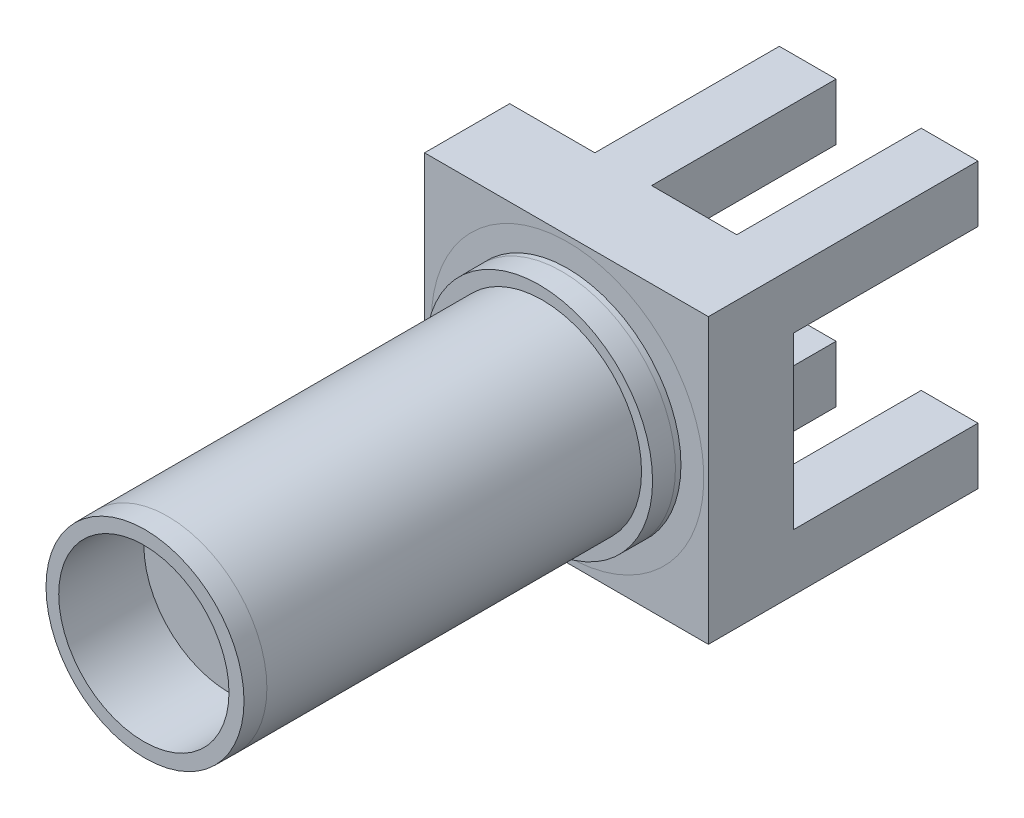
SolidWorks part; units mm, degrees
ref_plane "Front Plane" through (0, 0, 0) normal (0, 0, 1) x (1, 0, 0)
ref_plane "Top Plane" through (0, 0, 0) normal (0, 1, 0) x (1, 0, 0)
ref_plane "Right Plane" through (0, 0, 0) normal (1, 0, 0) x (0, 0, -1)
sketch "Sketch1" plane through (0, 0, 0) normal (0, 0, 1) x (1, 0, 0)
  line L1 (-1.1462, 0) -> (-11.1462, 0)
  line L2 (-1.1462, 0) -> (-1.1462, 10)
  line L3 (-1.1462, 10) -> (-11.1462, 10)
  line L4 (-11.1462, 0) -> (-11.1462, 10)
  dimension "D1" = 10
  dimension "D2" = 10
extrude "Boss-Extrude1" add sketch "Sketch1" along normal blind 3 contours L2 L1 L4 L3
sketch "Sketch2" plane through (0, 0, 0) normal (0, 0, 1) x (1, 0, 0)
  line L0 (-1.1462, 10) -> (-11.1462, 10) construction
  line L2 (-1.1462, 0) -> (-1.1462, 10) construction
  circle A0 centre (-6.1462, 5) radius 2.5
  dimension "D1" = 5
  dimension "D2" = 5
  dimension "D3" = 5
revolve "Cut-Revolve1" cut sketch "Sketch2" angle 7 about axis through (-1.1462, 0, 0) along (0, 1, 0)
sketch "Sketch3" plane through (0, 0, 0) normal (0, 0, -1) x (-1, 0, 0)
  line L1 (1.1462, 0) -> (3.1462, 0)
  line L2 (1.1462, 0) -> (1.1462, 2)
  line L3 (1.1462, 2) -> (3.1462, 2)
  line L4 (3.1462, 0) -> (3.1462, 2)
  dimension "D1" = 2
  dimension "D2" = 2
extrude "Boss-Extrude2" add sketch "Sketch3" along normal blind 6.5 contours L2 L1 L4 L3
sketch "Sketch4" plane through (0, 0, 0) normal (0, 0, -1) x (-1, 0, 0)
  line L1 (3.1462, 0) -> (11.1462, 0) construction
  line L3 (6.1462, 0) -> (8.1462, 0)
  line L4 (6.1462, 0) -> (6.1462, 2)
  line L5 (6.1462, 2) -> (8.1462, 2)
  line L6 (8.1462, 0) -> (8.1462, 2)
  dimension "D2" = 2
  dimension "D3" = 2
extrude "Boss-Extrude3" add sketch "Sketch4" along normal blind 6.5 contours L4 L3 L6 L5
sketch "Sketch5" plane through (0, 0, 0) normal (0, 0, -1) x (-1, 0, 0)
  line L2 (1.1462, 10) -> (3.1462, 10)
  line L3 (1.1462, 10) -> (1.1462, 8)
  line L4 (1.1462, 8) -> (3.1462, 8)
  line L5 (3.1462, 10) -> (3.1462, 8)
  line L6 (1.1462, 10) -> (11.1462, 10) construction
  line L8 (6.1462, 10) -> (8.1462, 10)
  line L9 (6.1462, 10) -> (6.1462, 8)
  line L10 (6.1462, 8) -> (8.1462, 8)
  line L11 (8.1462, 10) -> (8.1462, 8)
  dimension "D1" = 2
  dimension "D2" = 2
  dimension "D3" = 3
  dimension "D4" = 2
  dimension "D5" = 2
extrude "Boss-Extrude4" add sketch "Sketch5" along normal blind 6.5
sketch "Sketch6" plane through (0, 0, 0) normal (0, 0, -1) x (-1, 0, 0)
  line L0 (6.1462, 8) -> (6.1462, 2)
  circle A0 centre (6.1462, 5) radius 1
extrude "Boss-Extrude5" add sketch "Sketch6" along normal blind 6.5 separate body contours A0
chamfer "Chamfer2" distance 0.2 angle 45 1 edges at (-7.1462, 5, -6.5)
sketch "Sketch7" plane through (0, 0, 3) normal (0, 0, 1) x (1, 0, 0)
  circle A0 centre (-6.1062, 5) radius 4
extrude "Boss-Extrude6" add sketch "Sketch7" along normal blind 1 contours A0
chamfer "Chamfer10" distance 0.8 angle 0.45 2 edges at (-2.1062, 5, 3) (-2.1062, 5, 4)
sketch "Sketch9" plane through (0, 0, 4) normal (0, 0, 1) x (1, 0, 0)
  circle A0 centre (-5.996, 5.0893) radius 3.4948
  dimension "D1" = 6.9897
extrude "Boss-Extrude7" add sketch "Sketch9" along normal blind 14 contours A0
chamfer "Chamfer11" distance 0.8 angle 0.45 1 edges at (-2.5012, 5.0893, 18)
sketch "Sketch10" plane through (0, 0, 18) normal (0, 0, 1) x (1, 0, 0)
  circle A0 centre (-5.996, 5.0893) radius 3.4766
  dimension "D1" = 6.9531
sketch "Sketch11" plane through (0, 0, 18) normal (0, 0, 1) x (1, 0, 0)
  circle A0 centre (-6.037, 5.085) radius 3
extrude "Cut-Extrude1" cut sketch "Sketch11" against normal blind 3 contours A0
sketch "Sketch12" plane through (0, 0, 15) normal (0, 0, 1) x (1, 0, 0)
  circle A0 centre (-6.0574, 4.9162) radius 0.75
extrude "Cut-Extrude2" cut sketch "Sketch12" against normal blind 1 contours A0
